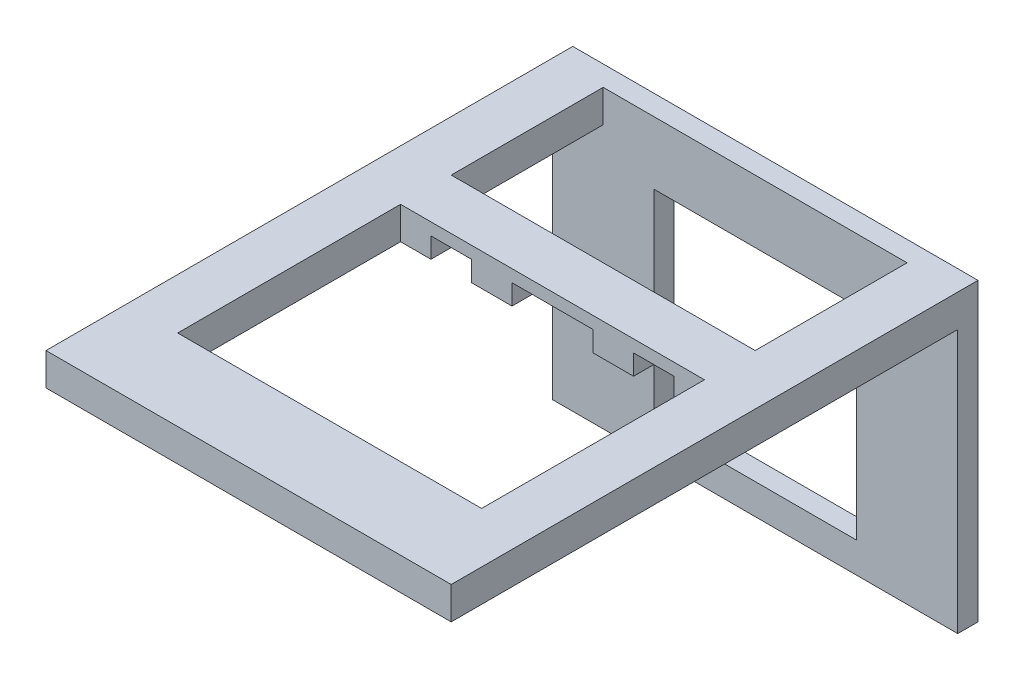
SolidWorks part; units mm, degrees
ref_plane "前视基准面" through (0, 0, 0) normal (0, 0, 1) x (1, 0, 0)
ref_plane "上视基准面" through (0, 0, 0) normal (0, 1, 0) x (1, 0, 0)
ref_plane "右视基准面" through (0, 0, 0) normal (1, 0, 0) x (0, 0, -1)
other "Configuration Table"
sketch "草图3" plane through (0, 0, 0) normal (0, 0, 1) x (1, 0, 0)
  line L0 (5, -2.3971) -> (5, 9.1029)
  line L2 (-5, 7.6029) -> (5, 7.6029)
  line L11 (-5, -2.3971) -> (-5, 9.1029)
  line L12 (5, -2.3971) -> (-5, -2.3971)
  line L17 (10, 9.1029) -> (-10, 9.1029)
  line L18 (10, 9.1029) -> (10, -3.8971)
  line L19 (10, -3.8971) -> (-10, -3.8971)
  line L20 (-10, 9.1029) -> (-10, -3.8971)
  arc A2 (2.9155, -2.1471) -> (-2.9155, -2.1471) centre (0, 1.6029) ccw construction
  dimension "D2" = 1.5
  dimension "D3" = 20
  dimension "D4" = 10
  dimension "D5" = 7.5
  dimension "D1" = 11.5
  dimension "D6" = 10
  dimension "D8" = 1.5
  dimension "D7" = 5
extrude "凸台-拉伸1" add sketch "草图3" along normal blind 1
sketch "草图4" plane through (0, 9.1029, 0) normal (0, 1, 0) x (1, 0, 0)
  line L1 (10, 0) -> (-10, 0)
  line L2 (10, 0) -> (10, -26)
  line L3 (10, -26) -> (-10, -26)
  line L4 (-10, 0) -> (-10, -26)
  line L6 (7.5, -1) -> (7.5, -8.5)
  line L7 (7.5, -8.5) -> (-7.5, -8.5)
  line L8 (-7.5, -1) -> (-7.5, -8.5)
  line L9 (10, -1) -> (-10, -1)
  line L10 (7.5, -22) -> (-7.5, -22)
  line L11 (7.5, -11) -> (-7.5, -11)
  line L12 (7.5, -11) -> (7.5, -22)
  line L13 (-7.5, -11) -> (-7.5, -22)
  line L14 (0, 0) -> (0, -26) construction
  point P18 (0, -8.5)
  point P26 (0, -22)
  line M15 (10, 0) -> (-10, 0)
  line M16 (-10, 0) -> (-10, -1)
  line M17 (-10, -1) -> (10, -1)
  line M18 (10, -1) -> (10, 0)
  dimension "D1" = 26
  dimension "D2" = 2.5
  dimension "D3" = 7.5
  dimension "D4" = 2.5
  dimension "D5" = 4
extrude "凸台-拉伸2" add sketch "草图4" along normal blind 1.6 contours L14 L9 M15 M17 M18 | L14 L1 M16 M17 | L14 L7 L8 L4 L3 L10 L13 L11 M17 | L7 L14 L11 L12 L10 L3 L2 L6 M17
sketch "草图6" plane through (0, 0, 1) normal (0, 0, 1) x (1, 0, 0)
  line L1 (-6, 10.1029) -> (-4, 10.1029)
  line L2 (-6, 10.1029) -> (-6, 9.1029)
  line L3 (-6, 9.1029) -> (-4, 9.1029)
  line L4 (-4, 10.1029) -> (-4, 9.1029)
  line L5 (4, 10.1029) -> (6, 10.1029)
  line L6 (4, 10.1029) -> (4, 9.1029)
  line L7 (4, 9.1029) -> (6, 9.1029)
  line L8 (6, 10.1029) -> (6, 9.1029)
  line L9 (10, 9.1029) -> (-10, 9.1029) construction
  line L10 (-2, 10.1029) -> (2, 10.1029)
  line L11 (-2, 10.1029) -> (-2, 9.1029)
  line L12 (-2, 9.1029) -> (2, 9.1029)
  line L13 (2, 10.1029) -> (2, 9.1029)
  line L16 (0, 10.7029) -> (0, 9.1029) construction
  line L17 (10, 10.7029) -> (-10, 10.7029) construction
  dimension "D1" = 1
  dimension "D2" = 4
  dimension "D3" = 2
  dimension "D4" = 2
extrude "切除-拉伸1" cut sketch "草图6" along normal up to next
